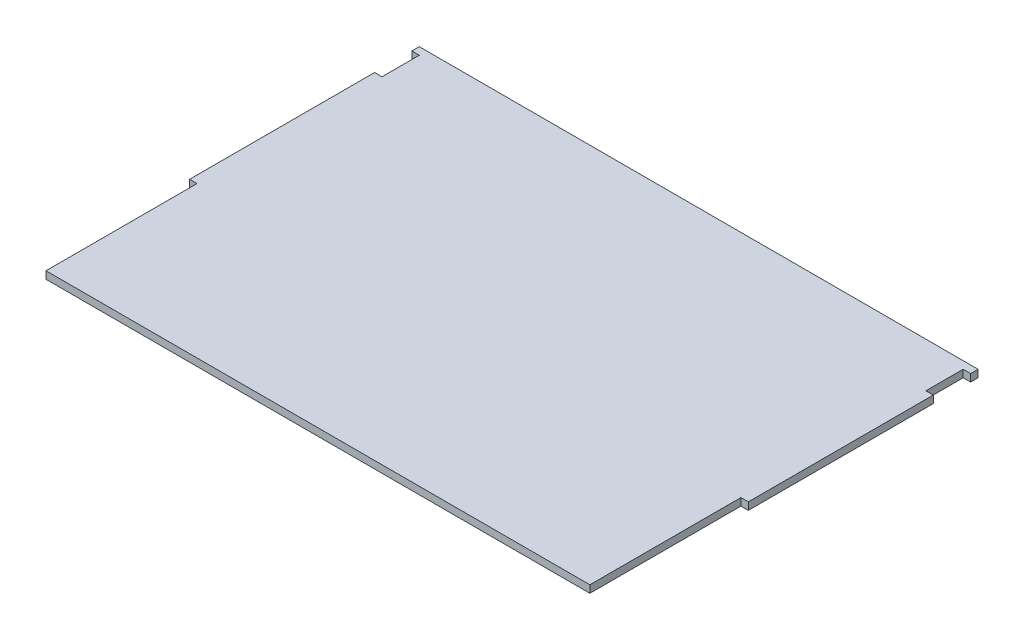
SolidWorks part; units mm, degrees
ref_plane "Front Plane" through (0, 0, 0) normal (0, 0, 1) x (1, 0, 0)
ref_plane "Top Plane" through (0, 0, 0) normal (0, 1, 0) x (1, 0, 0)
ref_plane "Right Plane" through (0, 0, 0) normal (1, 0, 0) x (0, 0, -1)
sketch "Sketch1" plane through (0, 0, 0) normal (0, 1, 0) x (1, 0, 0)
  line L0 (0, 154) -> (-3, 154)
  line L1 (0, 0) -> (220, 0)
  line L2 (0, 0) -> (0, 151)
  line L3 (0, 154) -> (220, 154)
  line L4 (220, 0) -> (220, 151)
  line L5 (-3, 154) -> (-3, 151)
  line L6 (-3, 151) -> (0, 151)
  line L7 (110, 154) -> (110, 0) construction
  line L8 (223, 154) -> (223, 151)
  line L9 (223, 151) -> (220, 151)
  line L10 (220, 154) -> (223, 154)
  dimension "D1" = 154
  dimension "D2" = 220
  dimension "D3" = 3
  dimension "D4" = 3
  dimension "D5" = 220
extrude "Boss-Extrude1" add sketch "Sketch1" along normal blind 3
sketch "Sketch2" plane through (223, 0, 0) normal (1, 0, 0) x (0, 0, -1)
  line L0 (151, 0) -> (154, 3) construction
  line L1 (154, 3) -> (151, 3) construction
  line L2 (151, 3) -> (154, 0) construction
  circle A0 centre (152.5, 1.5) radius 0.6169
  point P8 (152.5, 1.5)
sketch "Sketch3" plane through (0, 3, 0) normal (0, 1, 0) x (1, 0, 0)
  line L0 (0, 61.0882) -> (0, 135.9108) construction
  line L1 (0, 135.9108) -> (-3, 135.9108) construction
  line L2 (-3, 135.9108) -> (-3, 61.0882) construction
  line L3 (-3, 61.0882) -> (0, 61.0882) construction
  line L4 (223, 61.0882) -> (223, 135.9108) construction
  line L5 (223, 135.9108) -> (220, 135.9108) construction
  line L6 (220, 135.9108) -> (220, 61.0882) construction
  line L7 (220, 61.0882) -> (223, 61.0882) construction
  line L8 (0, 61.0882) -> (0, 135.9108)
  line L9 (0, 135.9108) -> (-3, 135.9108)
  line L10 (-3, 135.9108) -> (-3, 61.0882)
  line L11 (-3, 61.0882) -> (0, 61.0882)
  line L12 (223, 61.0882) -> (223, 135.9108)
  line L13 (223, 135.9108) -> (220, 135.9108)
  line L14 (220, 135.9108) -> (220, 61.0882)
  line L15 (220, 61.0882) -> (223, 61.0882)
extrude "Boss-Extrude2" add sketch "Sketch3" against normal up to surface (3 mm away) up to face at (110, 0, -114)
